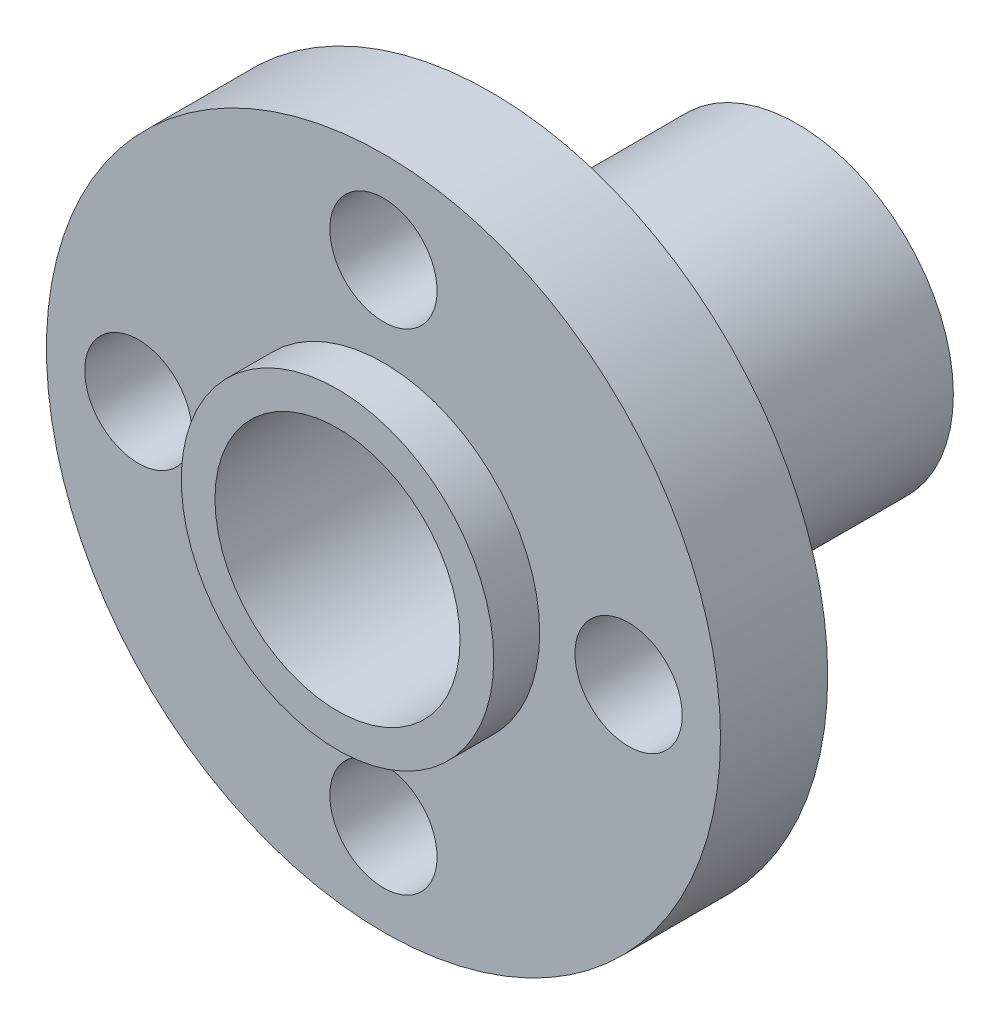
SolidWorks part; units mm, degrees
material "Brass"
ref_plane "Front Plane" through (0, 0, 0) normal (0, 0, 1) x (1, 0, 0)
ref_plane "Top Plane" through (0, 0, 0) normal (0, 1, 0) x (1, 0, 0)
ref_plane "Right Plane" through (0, 0, 0) normal (1, 0, 0) x (0, 0, -1)
sketch "Sketch1" plane through (0, 0, 0) normal (0, 0, 1) x (1, 0, 0)
  circle A0 centre (0, 0) radius 11
  circle A1 centre (0, 0) radius 8
  circle A2 centre (0, 8) radius 1.75
  circle A3 centre (8, 0) radius 1.75
  circle A4 centre (0, -8) radius 1.75
  circle A5 centre (-8, 0) radius 1.75
  circle A6 centre (0, 0) radius 4
  point P15 (0, 0)
  dimension "D1" = 22
  dimension "D2" = 16
  dimension "D3" = 3.5
  dimension "D5" = 8
  dimension "D4" = 4
extrude "Boss-Extrude1" add sketch "Sketch1" along normal blind 3.5 contours A0 A5 A1 A2 A3 A4 | A5 A1 A4 A3 A2 A6
sketch "Sketch2" plane through (0, 0, 0) normal (0, 0, -1) x (-1, 0, 0)
  circle A0 centre (0, 0) radius 5.1
  circle A1 centre (0, 0) radius 4
  dimension "D1" = 10.2
  dimension "D2" = 8
extrude "Boss-Extrude2" add sketch "Sketch2" along normal blind 10
sketch "Sketch3" plane through (0, 0, 3.5) normal (0, 0, 1) x (1, 0, 0)
  circle A0 centre (0, 0) radius 5.1
  circle A1 centre (0, 0) radius 4
  dimension "D1" = 10.2
  dimension "D2" = 8
extrude "Boss-Extrude3" add sketch "Sketch3" along normal blind 1.5
